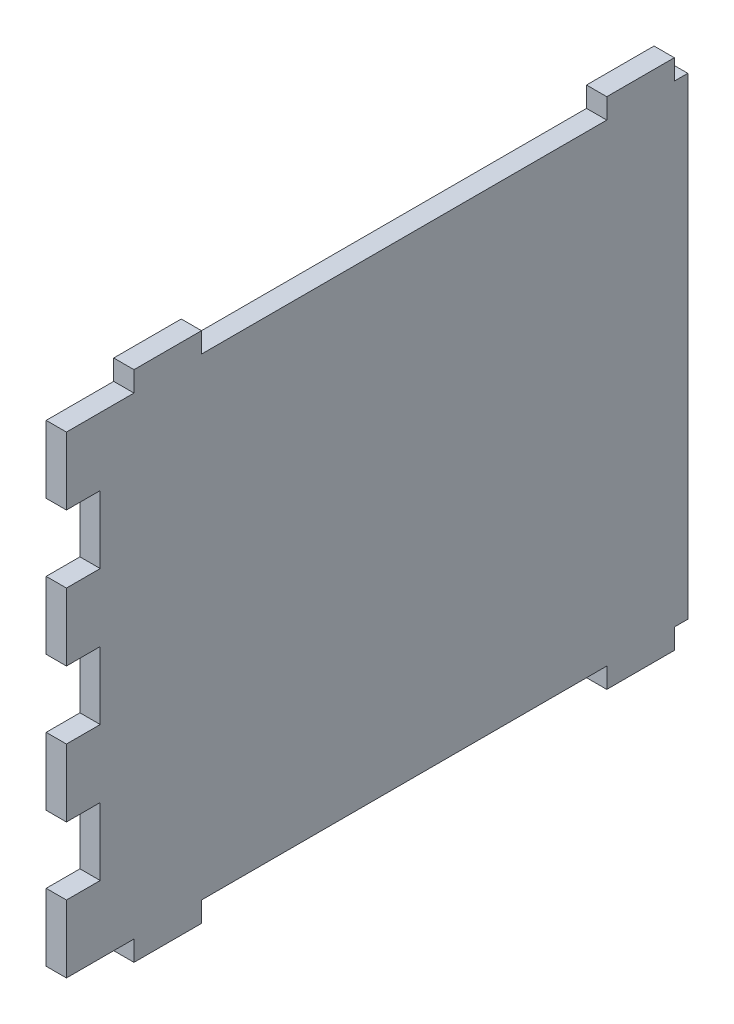
SolidWorks part; units mm, degrees
ref_plane "Plano frontal" through (0, 0, 0) normal (0, 0, 1) x (1, 0, 0)
ref_plane "Plano superior" through (0, 0, 0) normal (0, 1, 0) x (1, 0, 0)
ref_plane "Plano direito" through (0, 0, 0) normal (1, 0, 0) x (0, 0, -1)
sketch "Esboço1" plane through (0, 0, 0) normal (1, 0, 0) x (0, 0, -1)
  line L1 (-40, -35) -> (40, -35)
  line L2 (-40, -35) -> (-40, 35)
  line L3 (-40, 35) -> (40, 35)
  line L4 (40, -35) -> (40, 35)
  line L5 (-40, -35) -> (40, 35) construction
  line L6 (-40, 35) -> (40, -35) construction
  line L7 (-40, -35) -> (-30, -35)
  line L8 (-40, -35) -> (-40, -38)
  line L9 (-40, -38) -> (-30, -38)
  line L10 (-30, -35) -> (-30, -38)
  line L11 (40, -35) -> (30, -35)
  line L12 (40, -35) -> (40, -38)
  line L13 (40, -38) -> (30, -38)
  line L14 (30, -35) -> (30, -38)
  line L15 (40, 35) -> (30, 35)
  line L16 (40, 35) -> (40, 38)
  line L17 (40, 38) -> (30, 38)
  line L18 (30, 35) -> (30, 38)
  line L19 (-40, 35) -> (-30, 35)
  line L20 (-40, 35) -> (-40, 38)
  line L21 (-40, 38) -> (-30, 38)
  line L22 (-30, 35) -> (-30, 38)
  point P0 (0, 0)
  dimension "D1" = 70
  dimension "D2" = 80
  dimension "D3" = 3
  dimension "D4" = 3
  dimension "D5" = 3
  dimension "D6" = 3
  dimension "D7" = 10
  dimension "D8" = 10
  dimension "D9" = 10
  dimension "D10" = 10
extrude "Ressalto-extrusão1" add sketch "Esboço1" along normal blind 3 contours L3 L22 L21 L20 | L18 L3 L16 L17 | L1 L14 L13 L12 | L10 L1 L8 L9 | L1 L4 L3 L2
sketch "Esboço2" plane through (3, 0, 0) normal (1, 0, 0) x (0, 0, -1)
  line L0 (40, -38) -> (40, 38) construction
  line L1 (40, 35) -> (42, 35)
  line L2 (40, 35) -> (40, -35)
  line L3 (40, -35) -> (42, -35)
  line L4 (42, 35) -> (42, -35)
  line L6 (40, 38) -> (30, 38) construction
  dimension "D1" = 70
  dimension "D2" = 2
  dimension "D3" = 3
extrude "Ressalto-extrusão2" add sketch "Esboço2" against normal blind 3
sketch "Esboço3" plane through (3, 0, 0) normal (1, 0, 0) x (0, 0, -1)
  line L0 (-40, -38) -> (-40, 38) construction
  line L1 (-40, 35) -> (-45, 35)
  line L2 (-40, 35) -> (-40, -35)
  line L3 (-40, -35) -> (-45, -35)
  line L4 (-45, 35) -> (-45, -35)
  dimension "D1" = 70
  dimension "D2" = 3
  dimension "D3" = 5
extrude "Ressalto-extrusão3" add sketch "Esboço3" against normal blind 3
sketch "Esboço4" plane through (3, 0, 0) normal (1, 0, 0) x (0, 0, -1)
  line L0 (-45, 35) -> (-45, -35) construction
  line L1 (-45, 35) -> (-50, 35)
  line L2 (-45, 35) -> (-45, 25)
  line L3 (-45, 25) -> (-50, 25)
  line L4 (-50, 35) -> (-50, 25)
  line L5 (-45, 15) -> (-50, 15)
  line L6 (-45, 15) -> (-45, 5)
  line L7 (-45, 5) -> (-50, 5)
  line L8 (-50, 15) -> (-50, 5)
  line L10 (-45, -5) -> (-50, -5)
  line L11 (-45, -5) -> (-45, -15)
  line L12 (-45, -15) -> (-50, -15)
  line L13 (-50, -5) -> (-50, -15)
  line L14 (-45, -25) -> (-50, -25)
  line L15 (-45, -25) -> (-45, -35)
  line L16 (-45, -35) -> (-50, -35)
  line L17 (-50, -25) -> (-50, -35)
  dimension "D1" = 5
  dimension "D2" = 10
  dimension "D3" = 10
  dimension "D4" = 5
  dimension "D5" = 10
  dimension "D6" = 10
  dimension "D7" = 5
  dimension "D8" = 10
  dimension "D9" = 10
  dimension "D10" = 5
  dimension "D11" = 10
extrude "Ressalto-extrusão4" add sketch "Esboço4" against normal blind 3
